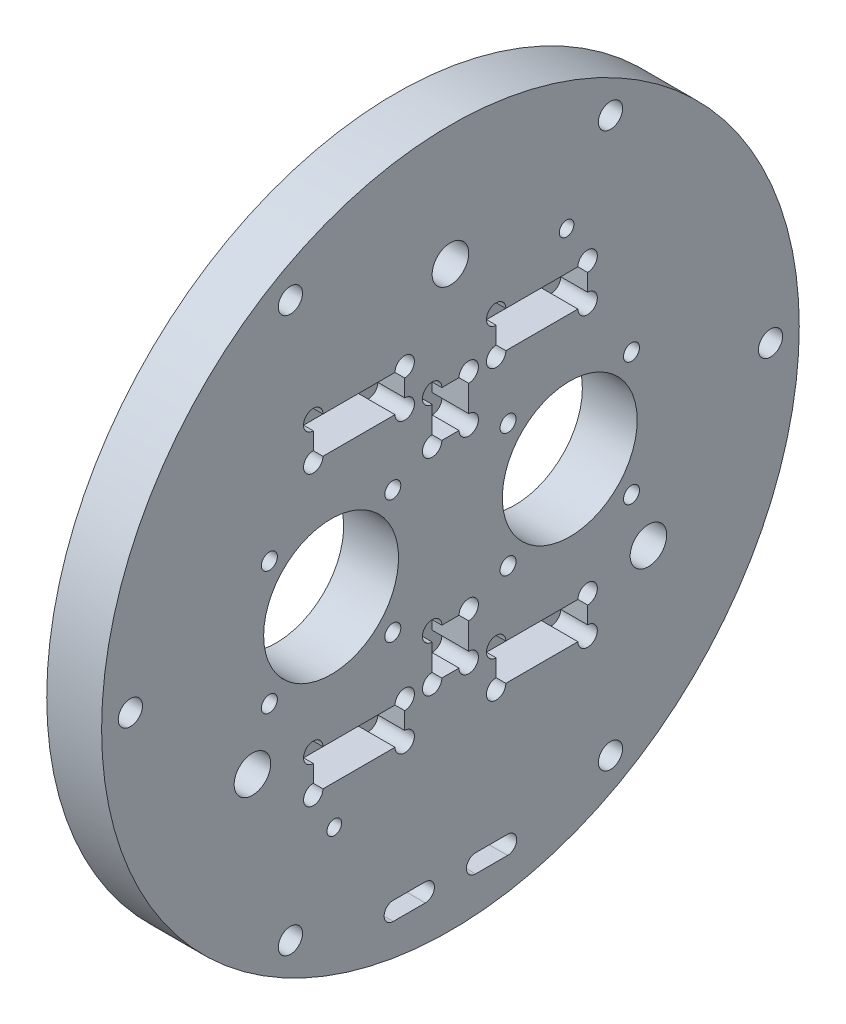
SolidWorks part; units mm, degrees
ref_plane "Front Plane" through (0, 0, 0) normal (0, 0, 1) x (1, 0, 0)
ref_plane "Top Plane" through (0, 0, 0) normal (0, 1, 0) x (1, 0, 0)
ref_plane "Right Plane" through (0, 0, 0) normal (1, 0, 0) x (0, 0, -1)
sketch "Sketch1" plane through (0, 0, 0) normal (1, 0, 0) x (0, 0, -1)
  line L0 (0, -76.29) -> (0, 76.29) construction
  line L1 (-76.29, 0) -> (76.29, 0) construction
  line L2 (26.1, 0) -> (39.5969, 13.4969) construction
  circle A0 centre (0, 0) radius 76.29
  circle A1 centre (0, 50) radius 4
  circle A2 centre (43.3013, -25) radius 4
  circle A3 centre (-43.3013, -25) radius 4
  circle A4 centre (26.1, 0) radius 14.75
  circle A5 centre (-26.1, 0) radius 14.75
  circle A6 centre (39.5969, 13.4969) radius 1.75
  circle A7 centre (39.5969, -13.4969) radius 1.75
  circle A8 centre (12.6031, -13.4969) radius 1.75
  circle A9 centre (12.6031, 13.4969) radius 1.75
  circle A10 centre (-39.5969, -13.4969) radius 1.75
  circle A11 centre (-12.6031, -13.4969) radius 1.75
  circle A12 centre (-12.6031, 13.4969) radius 1.75
  circle A13 centre (-39.5969, 13.4969) radius 1.75
  circle A14 centre (26.1, 0) radius 22.1 construction
  circle A15 centre (-26.1, 0) radius 22.1 construction
  point P12 (0, 0)
  point P29 (26.1, 0)
  point P37 (-4, 0)
  point P40 (4, 0)
  dimension "D1" = 152.58
  dimension "D2" = 8
  dimension "D5" = 29.5
  dimension "D7" = 3.5
  dimension "D11" = 44.2
  dimension "D3" = 50
  dimension "D4" = 3
  dimension "D6" = 8
  dimension "D8" = 19.0875
  dimension "D10" = 45
  dimension "D9" = 4
extrude "Boss-Extrude1" add sketch "Sketch1" along normal blind 12
sketch "Sketch2" plane through (12, 0, 0) normal (1, 0, 0) x (0, 0, -1)
  line L0 (-97.5918, 0) -> (102.3086, 0) construction
  line L1 (0, 96.3466) -> (0, -103.9448) construction
  line L2 (10, -27.5) -> (10, -35.5)
  line L3 (-30, -27.5) -> (-10, -27.5)
  line L4 (-30, -27.5) -> (-30, -35.5)
  line L5 (-30, -35.5) -> (-10, -35.5)
  line L6 (-10, -27.5) -> (-10, -35.5)
  line L7 (30, -27.5) -> (10, -27.5)
  line L8 (30, -27.5) -> (30, -35.5)
  line L9 (30, -35.5) -> (10, -35.5)
  line L10 (-30, 27.5) -> (-30, 35.5)
  line L11 (-30, 35.5) -> (-10, 35.5)
  line L12 (-10, 27.5) -> (-10, 35.5)
  line L13 (-30, 27.5) -> (-10, 27.5)
  line L14 (10, 27.5) -> (10, 35.5)
  line L15 (30, 35.5) -> (10, 35.5)
  line L16 (30, 27.5) -> (10, 27.5)
  line L17 (30, 27.5) -> (30, 35.5)
  line L18 (-4, -17.5) -> (4, -17.5)
  line L19 (-4, 27.5) -> (4, 27.5)
  line L20 (-4, 27.5) -> (-4, 17.5)
  line L21 (-4, 17.5) -> (4, 17.5)
  line L22 (4, 27.5) -> (4, 17.5)
  line L23 (-4, -27.5) -> (-4, -17.5)
  line L24 (-4, -27.5) -> (4, -27.5)
  line L25 (4, -27.5) -> (4, -17.5)
  line L26 (27.8787, -35.5) -> (30, -33.3787) construction
  line L27 (-42.3534, -68.29) -> (39.6493, -68.29) construction
  line L28 (-5.5, -68.29) -> (-5.5, -64.29)
  line L29 (12.5, -68.29) -> (5.5, -68.29)
  line L30 (12.5, -68.29) -> (12.5, -64.29)
  line L31 (12.5, -64.29) -> (5.5, -64.29)
  line L32 (5.5, -68.29) -> (5.5, -64.29)
  line L33 (-12.5, -64.29) -> (-5.5, -64.29)
  line L34 (-12.5, -68.29) -> (-12.5, -64.29)
  line L35 (-12.5, -68.29) -> (-5.5, -68.29)
  circle A0 centre (30, -35.5) radius 2.1213 construction
  circle A1 centre (0, 0) radius 76.29 construction
  point P23 (0, 27.5)
  point P31 (30, -33.3787)
  point P32 (0, -76.29)
  point P33 (27.8787, -35.5)
  dimension "D1" = 27.5
  dimension "D2" = 8
  dimension "D3" = 20
  dimension "D4" = 20
  dimension "D5" = 8
  dimension "D6" = 10
  dimension "D7" = 8
  dimension "D8" = 4
  dimension "D9" = 7
  dimension "D10" = 25
extrude "Cut-Extrude1" cut sketch "Sketch2" against normal blind 8
sketch "Sketch3" plane through (0, 0, 0) normal (-1, 0, 0) x (0, 0, 1)
  circle A0 centre (-70, 0) radius 2.65
  circle A1 centre (-35, 60.6218) radius 2.65
  circle A2 centre (35, 60.6218) radius 2.65
  circle A3 centre (70, 0) radius 2.65
  circle A4 centre (35, -60.6218) radius 2.65
  circle A5 centre (-35, -60.6218) radius 2.65
  point P16 (0, 0)
  dimension "D2" = 5.3
  dimension "D1" = 70
  dimension "D3" = 6
extrude "Cut-Extrude2" cut sketch "Sketch3" against normal up to next
sketch "Sketch4" plane through (12, 0, 0) normal (1, 0, 0) x (0, 0, -1)
  line L0 (12.5, -68.29) -> (12.5, -64.29) construction
  line L2 (5.5, -64.29) -> (5.5, -68.29) construction
  line L3 (-5.5, -68.29) -> (-5.5, -64.29) construction
  line L4 (-12.5, -64.29) -> (-12.5, -68.29) construction
  circle A0 centre (-10, -35.5) radius 2.1213
  circle A1 centre (-10, -27.5) radius 2.1213
  circle A2 centre (-30, -27.5) radius 2.1213
  circle A3 centre (-30, -35.5) radius 2.1213
  circle A4 centre (12.5, -66.29) radius 2
  circle A5 centre (5.5, -66.29) radius 2
  circle A6 centre (-5.5, -66.29) radius 2
  circle A7 centre (-12.5, -66.29) radius 2
  circle A12 centre (10, -35.5) radius 2.1213
  circle A13 centre (10, -27.5) radius 2.1213
  circle A14 centre (30, -27.5) radius 2.1213
  circle A15 centre (30, -35.5) radius 2.1213
  circle A16 centre (4, -27.5) radius 2.1213
  circle A17 centre (-4, -27.5) radius 2.1213
  circle A18 centre (-4, -17.5) radius 2.1213
  circle A19 centre (4, -17.5) radius 2.1213
  circle A20 centre (4, 27.5) radius 2.1213
  circle A21 centre (-4, 27.5) radius 2.1213
  circle A22 centre (-4, 17.5) radius 2.1213
  circle A23 centre (4, 17.5) radius 2.1213
  circle A24 centre (10, 27.5) radius 2.1213
  circle A25 centre (10, 35.5) radius 2.1213
  circle A26 centre (30, 35.5) radius 2.1213
  circle A27 centre (30, 27.5) radius 2.1213
  circle A28 centre (-10, 35.5) radius 2.1213
  circle A29 centre (-10, 27.5) radius 2.1213
  circle A30 centre (-30, 27.5) radius 2.1213
  circle A31 centre (-30, 35.5) radius 2.1213
  point P2 (-12.1213, -35.5)
  point P5 (-10, -33.3787)
  dimension "D1" = 3
extrude "Cut-Extrude3" cut sketch "Sketch4" against normal up to surface (8 mm away) up to face at (4, -31.5, 20)
sketch "Sketch5" plane through (0, 0, 0) normal (-1, 0, 0) x (0, 0, 1)
  line L0 (35, -60.6218) -> (-35, 60.6218) construction
  line L1 (0, 113.7201) -> (0, -122.5246) construction
  line L2 (-128.5049, 0) -> (121.7105, 0) construction
  circle A0 centre (35, -60.6218) radius 2.65 construction
  circle A1 centre (25.4034, -44) radius 1.6
  circle A2 centre (-25.4034, 44) radius 1.6
  point P7 (0, 0)
  point P12 (0, 0)
  dimension "D2" = 3.2
  dimension "D1" = 2
  dimension "D3" = 44
  dimension "D4" = 50.8068
extrude "Cut-Extrude4" cut sketch "Sketch5" against normal up to next
